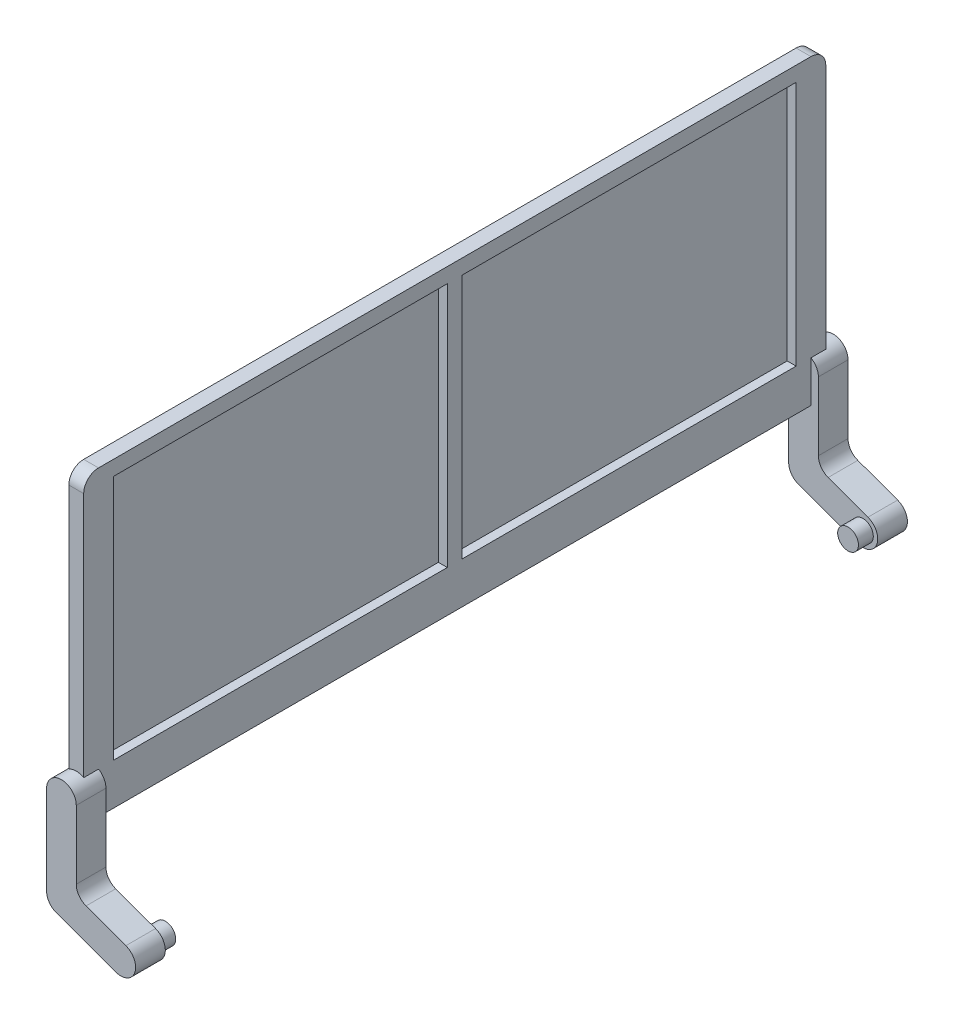
SolidWorks part; units mm, degrees
material "Glass"
ref_plane "Front Plane" through (0, 0, 0) normal (0, 0, 1) x (1, 0, 0)
ref_plane "Top Plane" through (0, 0, 0) normal (0, 1, 0) x (1, 0, 0)
ref_plane "Right Plane" through (0, 0, 0) normal (1, 0, 0) x (0, 0, -1)
sketch "Sketch1" plane through (0, 0, 0) normal (1, 0, 0) x (0, 0, -1)
  line L0 (0, 0) -> (0, 101.8) construction
  line L1 (-120, 101.8) -> (120, 101.8)
  line L2 (-125, 96.8) -> (-125, 0)
  line L3 (-125, 0) -> (125, 0)
  line L4 (125, 96.8) -> (125, 0)
  line L5 (115, 14) -> (2.5, 14)
  line L6 (-115, 96.8) -> (-2.5, 96.8)
  line L7 (-115, 96.8) -> (-115, 14)
  line L8 (-115, 14) -> (-2.5, 14)
  line L9 (-2.5, 96.8) -> (-2.5, 14)
  line L10 (115, 96.8) -> (115, 14)
  line L11 (115, 96.8) -> (2.5, 96.8)
  line L12 (2.5, 96.8) -> (2.5, 14)
  arc A0 (120, 101.8) -> (125, 96.8) centre (120, 96.8) cw
  arc A1 (-120, 101.8) -> (-125, 96.8) centre (-120, 96.8) ccw
  point P17 (125, 101.8)
  dimension "D7" = 5
  dimension "D1" = 250
  dimension "D2" = 101.8
  dimension "D3" = 5
  dimension "D4" = 14
  dimension "D5" = 10
  dimension "D6" = 5
extrude "Boss-Extrude1" add sketch "Sketch1" against normal blind 5
sketch "Sketch2" plane through (0, 0, 125) normal (0, 0, 1) x (1, 0, 0)
  line L0 (-5, 0) -> (0, 0)
  line L1 (0, 0) -> (-5, 1.8199)
  line L2 (-5, 96.8) -> (-5, 0) construction
  line L3 (-5, 1.8199) -> (-5, 0)
  line L4 (0, 96.8) -> (0, 0) construction
  dimension "D1" = 110
extrude "Cut-Extrude1" cut sketch "Sketch2" against normal through all
sketch "Sketch3" plane through (0, 0, 125) normal (0, 0, 1) x (1, 0, 0)
  line L0 (-2.5, 9.6) -> (-2.5, -20.4) construction
  line L1 (-2.5, -20.4) -> (17.5, -27.6794) construction
  line L3 (-5, 101.8) -> (0, 101.8) construction
  line L4 (-7.5, 9.6) -> (-7.5, -20.4)
  line L5 (-4.2101, -25.0985) -> (15.7899, -32.3779)
  line L6 (2.5, 9.6) -> (2.5, -13.3979)
  line L7 (5.7899, -18.0964) -> (19.2101, -22.9809)
  line L8 (-7.5, 9.6) -> (-7.5, -23.901) construction
  line L9 (-7.5, -23.901) -> (15.7899, -32.3779) construction
  line L10 (2.5, 9.6) -> (2.5, -16.899) construction
  line L11 (2.5, -16.899) -> (19.2101, -22.9809) construction
  arc A0 (-7.5, 9.6) -> (2.5, 9.6) centre (-2.5, 9.6) cw
  arc A1 (15.7899, -32.3779) -> (19.2101, -22.9809) centre (17.5, -27.6794) ccw
  arc A2 (-7.5, -20.4) -> (-4.2101, -25.0985) centre (-2.5, -20.4) ccw
  arc A3 (2.5, -13.3979) -> (5.7899, -18.0964) centre (7.5, -13.3979) ccw
  dimension "D8" = 5
  dimension "D1" = 30
  dimension "D2" = 20
  dimension "D3" = 2.5
  dimension "D4" = 92.2
  dimension "D5" = 110
  dimension "D6" = 5
  dimension "D7" = 5
extrude "Boss-Extrude2" add sketch "Sketch3" along normal mid plane 10 separate body
sketch "Sketch4" plane through (0, 0, 120) normal (0, 0, -1) x (-1, 0, 0)
  circle A0 centre (-17.5, -27.6794) radius 3.5
  dimension "D1" = 7
extrude "Boss-Extrude3" add sketch "Sketch4" along normal blind 5
mirror "Mirror1" about plane through (0, 0, 0) normal (0, 0, 1) of bodies 104
chamfer "Chamfer3" distance 2 angle 45 8 edges at (-5, 55.4, -115) (-5, 96.8, -58.75) (-5, 55.4, -2.5) (-5, 14, -58.75) (-5, 55.4, 115) (-5, 96.8, 58.75) (-5, 14, 58.75) (-5, 55.4, 2.5)
ref_plane "Plane1" through (-5, 98.8, -117) normal (0, 1, 0) x (1, 0, 0)
sketch "Sketch6" plane through (-5, 0, 0) normal (-1, 0, 0) x (0, 0, 1)
  line L4 (117, 98.8) -> (0.5, 98.8)
  line L5 (117, 12) -> (117, 98.8)
  line L6 (0.5, 12) -> (117, 12)
  line L7 (0.5, 98.8) -> (0.5, 12)
  line L8 (117, 98.8) -> (0.5, 98.8)
  line L9 (117, 12) -> (117, 98.8)
  line L10 (0.5, 12) -> (117, 12)
  line L11 (0.5, 98.8) -> (0.5, 12)
  line L12 (-117, 12) -> (-0.5, 12)
  line L13 (-117, 98.8) -> (-117, 12)
  line L14 (-0.5, 98.8) -> (-117, 98.8)
  line L15 (-0.5, 12) -> (-0.5, 98.8)
  line L16 (-117, 12) -> (-0.5, 12)
  line L17 (-117, 98.8) -> (-117, 12)
  line L18 (-0.5, 98.8) -> (-117, 98.8)
  line L19 (-0.5, 12) -> (-0.5, 98.8)
  dimension "D1" = 0
  dimension "D2" = 0
extrude "Boss-Extrude4" add sketch "Sketch6" against normal blind 1 separate body
